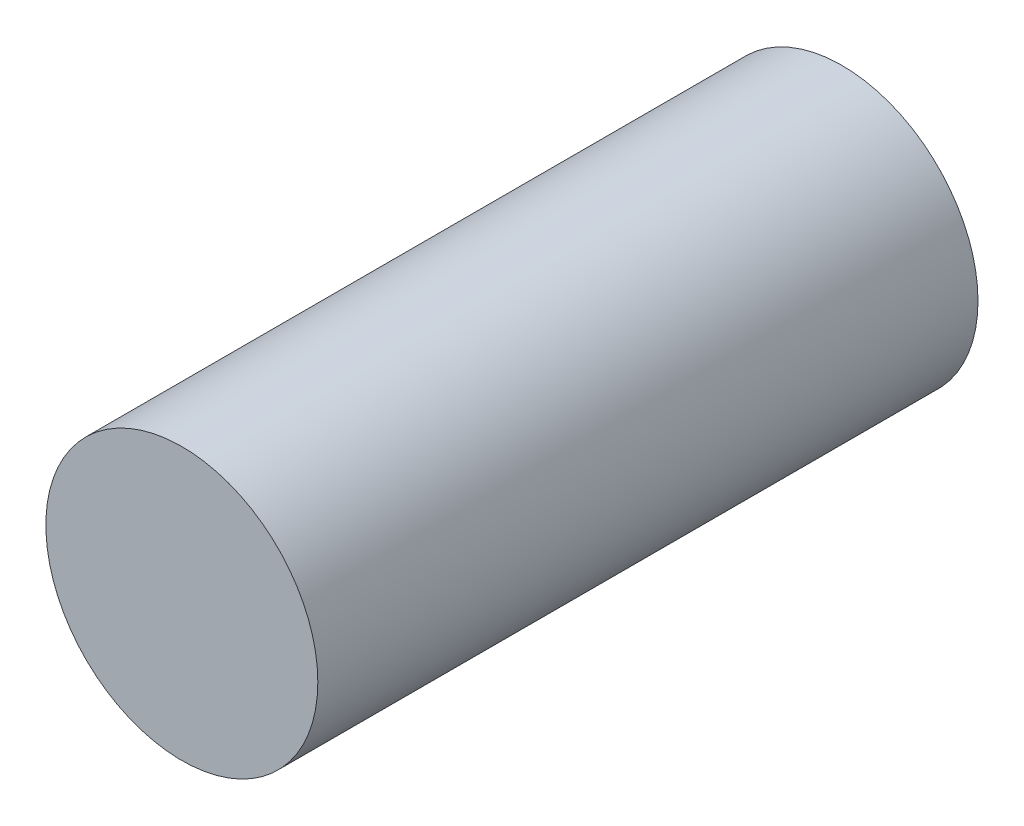
SolidWorks part; units mm, degrees
ref_plane "Front Plane" through (0, 0, 0) normal (0, 0, 1) x (1, 0, 0)
ref_plane "Top Plane" through (0, 0, 0) normal (0, 1, 0) x (1, 0, 0)
ref_plane "Right Plane" through (0, 0, 0) normal (1, 0, 0) x (0, 0, -1)
sketch "Sketch1" plane through (0, 0, 0) normal (0, 0, 1) x (1, 0, 0)
  circle A0 centre (0, 0) radius 2.06
  dimension "D1" = 4.12
extrude "Boss-Extrude1" add sketch "Sketch1" along normal blind 10
